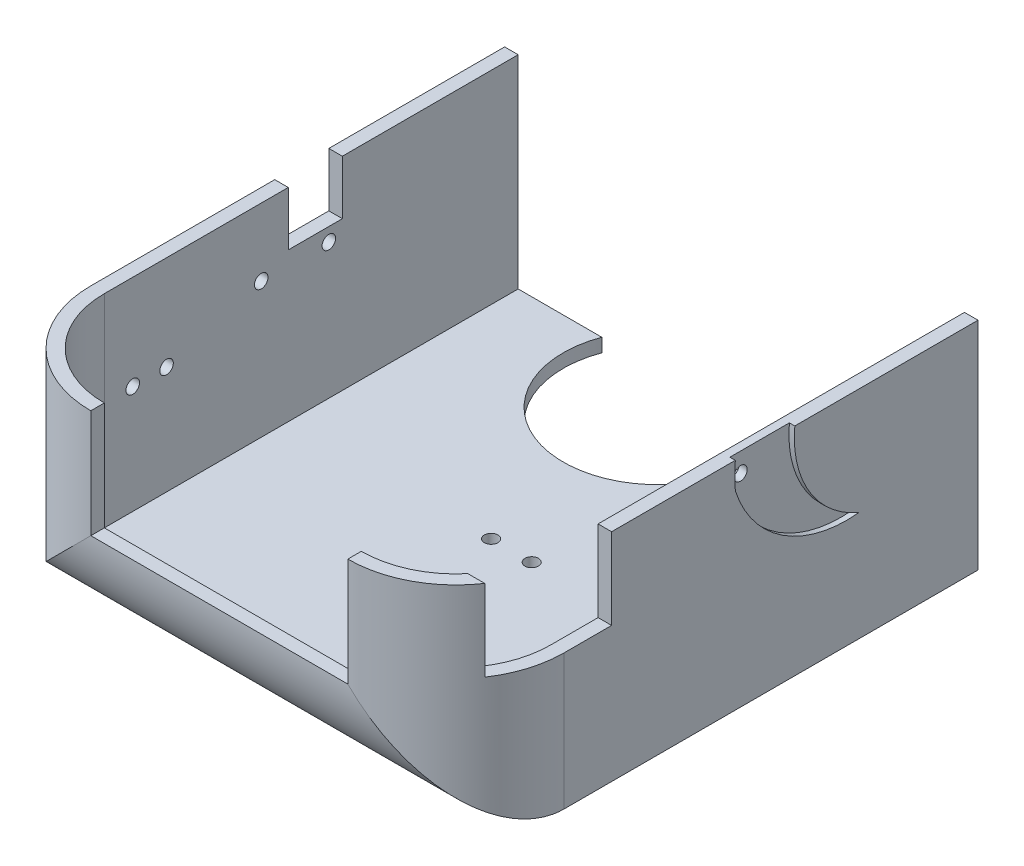
SolidWorks part; units mm, degrees
ref_plane "前基準面" through (0, 0, 0) normal (0, 0, 1) x (1, 0, 0)
ref_plane "上基準面" through (0, 0, 0) normal (0, 1, 0) x (1, 0, 0)
ref_plane "右基準面" through (0, 0, 0) normal (1, 0, 0) x (0, 0, -1)
sketch "草圖1" plane through (0, 0, 0) normal (0, 0, 1) x (1, 0, 0)
  line L1 (-87.5, -80) -> (87.5, -80)
  line L2 (-87.5, -80) -> (-87.5, 80)
  line L3 (-87.5, 80) -> (87.5, 80)
  line L4 (87.5, -80) -> (87.5, 80)
  line L5 (-87.5, -80) -> (87.5, 80) construction
  line L6 (-87.5, 80) -> (87.5, -80) construction
  point P0 (0, 0)
  dimension "D1" = 175
  dimension "D2" = 160
extrude "填料-伸長1" add sketch "草圖1" along normal blind 193
sketch "草圖4" plane through (0, 0, 0) normal (0, 1, 0) x (1, 0, 0)
  line L0 (0, 0) -> (0, -200)
  line L1 (0, -200) -> (-165, -200)
  line L2 (-165, -200) -> (-165, 0)
  line L3 (0, -200) -> (110, -200)
  line L4 (110, -200) -> (110, 0)
  line L5 (110, 0) -> (-165, 0)
  dimension "D1" = 165
  dimension "D2" = 200
sketch "草圖5" plane through (0, 0, 0) normal (1, 0, 0) x (0, 0, -1)
  line L0 (-200, 0) -> (-200, 160) construction
  line L1 (0, 0) -> (-200, 0) construction
  line L2 (-200, 160) -> (0, 160) construction
  dimension "D1" = 160
fillet "圓角8" radius 40 4 edges at (87.5, 0, 193) (0, 80, 193) (-87.5, 0, 193) (0, -80, 193)
shell "薄殼2" thickness 5
ref_plane "平面1" through (85, 0, 0) normal (1, 0, 0) x (0, 0, -1)
ref_plane "平面2" through (0, 80, 0) normal (0, 1, 0) x (1, 0, 0)
sketch "草圖8" plane through (0, 80, 0) normal (0, 1, 0) x (1, 0, 0)
  line L1 (87.5, 0) -> (-87.5, 0) construction
  line L3 (-87.5, 0) -> (17, 0) construction
  line L4 (-87.5, 0) -> (-87.5, -197.279) construction
  line L5 (-87.5, -197.279) -> (17, -197.279) construction
  line L6 (17, 0) -> (17, -197.279) construction
sketch "草圖9" plane through (0, 0, 193) normal (0, 0, 1) x (1, 0, 0)
  line L1 (-47.5, 40) -> (47.5, 40)
  line L2 (-47.5, 40) -> (-47.5, -40)
  line L3 (-47.5, -40) -> (47.5, -40)
  line L4 (47.5, 40) -> (47.5, -40)
extrude "除料-伸長3" cut sketch "草圖9" against normal blind 10
sketch "草圖10" plane through (0, 80, 0) normal (0, 1, 0) x (1, 0, 0)
  line L0 (0, 0) -> (-87.5, 0) construction
  line L1 (87.5, 0) -> (-87.5, 0) construction
  line L2 (-87.5, 0) -> (-43.75, 0) construction
  line L3 (-43.75, 0) -> (-87.5, 0) construction
  line L4 (-87.5, 0) -> (-65.625, 0) construction
  line L5 (-65.625, 0) -> (-43.75, -12.1031) construction
  line L6 (-43.75, 0) -> (-43.75, -31.8331) construction
  line L7 (-43.75, -12.1031) -> (-18.75, -12.1031)
  circle A0 centre (-18.75, -12.1031) radius 35
  dimension "D1" = 25
  dimension "D2" = 25
extrude "除料-伸長4" cut sketch "草圖10" against normal blind 160 contours A0
ref_plane "平面3" through (90, 0, 0) normal (1, 0, 0) x (0, 0, -1)
sketch "草圖12" plane through (90, 0, 0) normal (1, 0, 0) x (0, 0, -1)
  line L1 (-175.4577, -30) -> (-135.4577, 30) construction
  line L3 (-135.4577, -30) -> (-135.4577, 30)
  line L7 (-135.4577, 30) -> (-175.4577, 30)
  line L8 (-175.4577, 30) -> (-175.4577, -30)
  line L9 (-175.4577, -30) -> (-135.4577, -30)
  line L10 (0, 0) -> (-208.2911, 0) construction
  line L11 (-175.4577, 30) -> (-135.4577, -30) construction
  point P4 (-155.4577, 0)
  dimension "D1" = 60
  dimension "D2" = 40
extrude "除料-伸長5" cut sketch "草圖12" against normal blind 20
extrude "除料-伸長6" cut sketch "草圖4" along normal blind 80 contours L1 L2 L5 L4 L3
ref_plane "平面4" through (0, -80, 0) normal (0, 1, 0) x (1, 0, 0)
sketch "草圖15" plane through (0, -80, 0) normal (0, 1, 0) x (1, 0, 0)
  line L0 (0, 0) -> (0, -200) construction
  line L1 (-87.5, 0) -> (17, 0) construction
  line L3 (0, -85) -> (-15, -85) construction
  line L4 (-15, -85) -> (0, -85)
  line L5 (15, -85) -> (0, -85) construction
  circle A0 centre (0, -85) radius 15 construction
  circle A1 centre (-7.5, -85) radius 2.5
  circle A2 centre (7.5, -85) radius 2.5
  dimension "D1" = 85
extrude "除料-伸長8" cut sketch "草圖15" along normal blind 5 contours A1 | A2
sketch "草圖17" plane through (-87.5, 0, 0) normal (-1, 0, 0) x (0, 0, 1)
  line L0 (0, 0) -> (65, 0) construction
  line L1 (0, 0) -> (153, 0) construction
  line L2 (65, 0) -> (85, 0)
  line L3 (85, 0) -> (85, -20)
  line L4 (65, 0) -> (65, -20)
  line L5 (65, -20) -> (85, -20)
  line L6 (65, -20) -> (65, -30) construction
  line L7 (130, -30) -> (130, -35) construction
  line L8 (130, -35) -> (142.5, -35) construction
  line L9 (65, -30) -> (100, -30) construction
  line L10 (100, -30) -> (100, 0) construction
  line L11 (65, -25) -> (70, -25) construction
  line L12 (70, -25) -> (70, -30) construction
  line L13 (100, -25) -> (95, -25) construction
  circle A0 centre (130, -35) radius 2.5
  circle A1 centre (142.5, -35) radius 2.5
  circle A2 centre (70, -25) radius 2.5
  circle A3 centre (95, -25) radius 2.5
  dimension "D4" = 10
  dimension "D1" = 65
  dimension "D2" = 20
  dimension "D3" = 20
  dimension "D5" = 5
  dimension "D6" = 12.5
extrude "除料-伸長10" cut sketch "草圖17" against normal blind 5
sketch "草圖18" plane through (87.5, 0, 0) normal (1, 0, 0) x (0, 0, -1)
  line L0 (-135.4577, 0) -> (0, 0) construction
  line L1 (-89.7288, 0) -> (-67.7288, 0)
  line L2 (-89.894, -4.7715) -> (-89.7288, -9.7715)
  line L3 (-89.7288, 0) -> (-89.894, -4.7715)
  arc A2 (-89.7288, -9.7715) -> (-43.9773, -39.5692) centre (-48.5494, 3.4332) ccw
  arc A3 (-67.7288, 0) -> (-43.9773, -39.5692) centre (-29.0885, -3.7191) ccw
  dimension "D1" = 22
  dimension "D2" = 5
extrude "除料-伸長11" cut sketch "草圖18" against normal blind 2
sketch "草圖20" plane through (85.5, 0, 0) normal (1, 0, 0) x (0, 0, -1)
  line L0 (-89.894, -4.7715) -> (-89.7288, -9.7715)
  line L1 (-89.8114, -7.2715) -> (-85.8114, -7.1394)
  circle A0 centre (-85.8114, -7.1394) radius 2.5
  dimension "D1" = 4
extrude "除料-伸長13" cut sketch "草圖20" against normal blind 5 contours A0
